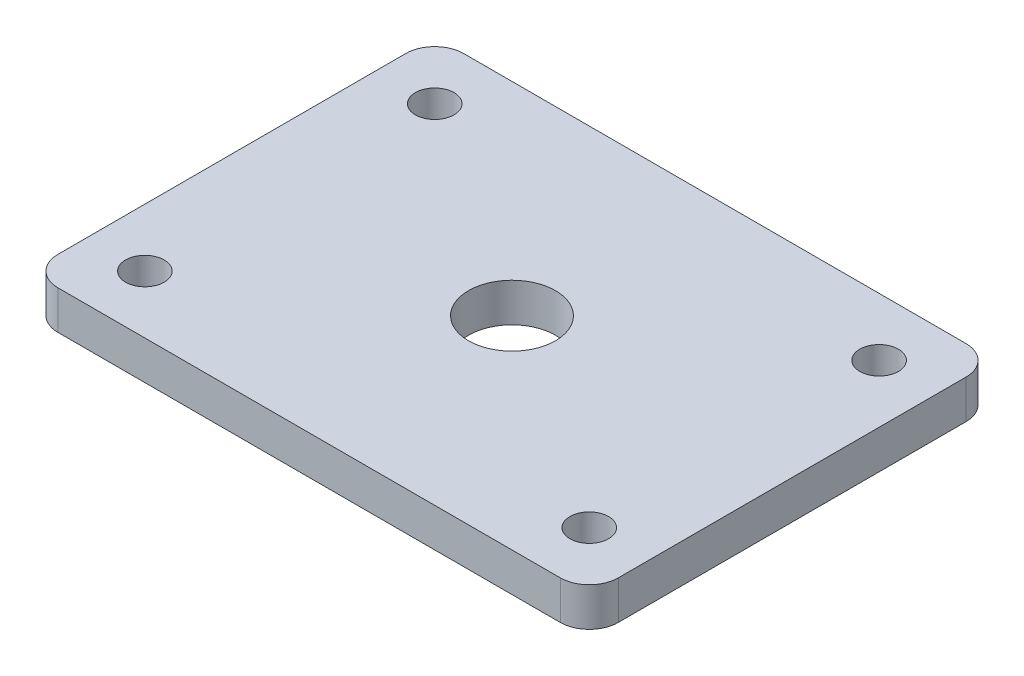
SolidWorks part; units mm, degrees
ref_plane "Front Plane" through (0, 0, 0) normal (0, 0, 1) x (1, 0, 0)
ref_plane "Top Plane" through (0, 0, 0) normal (0, 1, 0) x (1, 0, 0)
ref_plane "Right Plane" through (0, 0, 0) normal (1, 0, 0) x (0, 0, -1)
sketch "Sketch1" plane through (0, 0, 0) normal (0, 1, 0) x (1, 0, 0)
  line L1 (-23, 15) -> (23, 15)
  line L2 (-23, 15) -> (-23, -15)
  line L3 (-23, -15) -> (23, -15)
  line L4 (23, 15) -> (23, -15)
  line L5 (-23, 15) -> (23, -15) construction
  line L6 (-23, -15) -> (23, 15) construction
  line L7 (-29, 21) -> (29, 21)
  line L8 (-29, 21) -> (-29, -21)
  line L9 (-29, -21) -> (29, -21)
  line L10 (29, 21) -> (29, -21)
  line L11 (-29, 21) -> (29, -21) construction
  line L12 (-29, -21) -> (29, 21) construction
  circle A0 centre (-23, 15) radius 2
  circle A1 centre (23, 15) radius 2
  circle A2 centre (23, -15) radius 2
  circle A3 centre (-23, -15) radius 2
  circle A4 centre (0, 0) radius 4.5
  point P0 (0, 0)
  point P6 (0, 0)
  dimension "D5" = 4
  dimension "D6" = 4
  dimension "D7" = 4
  dimension "D8" = 4
  dimension "D9" = 9
  dimension "D1" = 30
  dimension "D2" = 46
  dimension "D3" = 6
  dimension "D4" = 6
extrude "Boss-Extrude1" add sketch "Sketch1" along normal blind 4 contours L10 L7 L8 L9 A3 L2 A0 L1 A1 L4 A2 L3 | A3 L3 A2 L4 A1 L1 A0 L2 A4
fillet "Fillet1" radius 3 4 edges at (29, 2, 21) (-29, 2, 21) (-29, 2, -21) (29, 2, -21)
